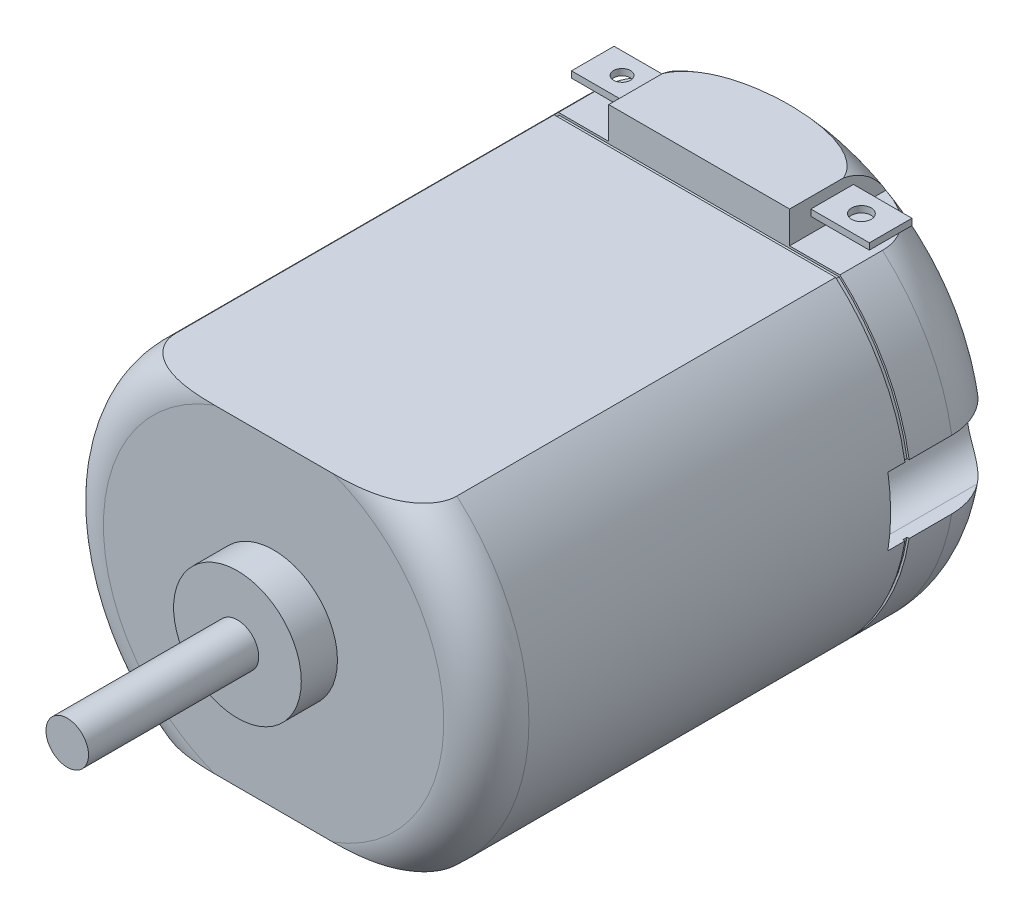
SolidWorks part; units mm, degrees
ref_plane "Спереди" through (0, 0, 0) normal (0, 0, 1) x (1, 0, 0)
ref_plane "Сверху" through (0, 0, 0) normal (0, 1, 0) x (1, 0, 0)
ref_plane "Справа" through (0, 0, 0) normal (1, 0, 0) x (0, 0, -1)
sketch "Эскиз1" plane through (0, 0, 0) normal (0, 0, 1) x (1, 0, 0)
  circle A0 centre (0, 0) radius 10
  dimension "D1" = 20
extrude "Бобышка-Вытянуть1" add sketch "Эскиз1" along normal blind 25
sketch "Эскиз2" plane through (0, 0, 0) normal (0, 0, 1) x (1, 0, 0)
  line L1 (12.9274, -7.5) -> (-12.9274, -7.5)
  line L2 (12.9274, -7.5) -> (12.9274, 7.5)
  line L3 (12.9274, 7.5) -> (-12.9274, 7.5)
  line L4 (-12.9274, -7.5) -> (-12.9274, 7.5)
  line L5 (12.9274, -7.5) -> (-12.9274, 7.5) construction
  line L6 (12.9274, 7.5) -> (-12.9274, -7.5) construction
  point P0 (0, 0)
  dimension "D1" = 15
extrude "Вырез-Вытянуть-Тонкостенный2" cut sketch "Эскиз2" along normal blind 25 from offset 5 thin thin type one direction wall 10
sketch "Эскиз3" plane through (0, 0, 25) normal (0, 0, 1) x (1, 0, 0)
  circle A0 centre (0, 0) radius 3
  dimension "D1" = 6
extrude "Бобышка-Вытянуть2" add sketch "Эскиз3" along normal blind 1.7
sketch "Эскиз4" plane through (0, 0, 26.7) normal (0, 0, 1) x (1, 0, 0)
  circle A0 centre (0, 0) radius 1
  dimension "D1" = 2
extrude "Бобышка-Вытянуть3" add sketch "Эскиз4" along normal blind 8
fillet "Скругление1" radius 2 2 edges at (10, 0, 25) (-10, 0, 25)
fillet "Скругление2" radius 3 1 edges at (10, 0, 0)
sketch "Эскиз5" plane through (0, 0, 0) normal (0, 0, -1) x (-1, 0, 0)
  line L0 (-3.5707, -3.5) -> (3.5707, -3.5)
  line L2 (-2.5, 3) -> (2.5, 3)
  line L3 (-2.5, 3) -> (-2.5, 2.2)
  line L4 (-2.5, 2.2) -> (2.5, 2.2)
  line L5 (2.5, 3) -> (2.5, 2.2)
  line L6 (-2.5, 3) -> (2.5, 2.2) construction
  line L7 (-2.5, 2.2) -> (2.5, 3) construction
  arc A0 (3.5707, -3.5) -> (-3.5707, -3.5) centre (0, 0) ccw
  point P5 (0, 2.6)
  dimension "D1" = 10
  dimension "D2" = 3.5
  dimension "D3" = 0.8
  dimension "D4" = 5
  dimension "D5" = 3
extrude "Бобышка-Вытянуть4" add sketch "Эскиз5" along normal blind 2
sketch "Эскиз6" plane through (0, 0, -2) normal (0, 0, -1) x (-1, 0, 0)
  circle A0 centre (0, 0) radius 1
  dimension "D1" = 2
extrude "Бобышка-Вытянуть5" add sketch "Эскиз6" along normal blind 1
sketch "Эскиз7" plane through (0, 0, 0) normal (0, 0, 1) x (1, 0, 0)
  line L0 (9.25, 0) -> (12.5108, 0) construction
  line L1 (9.25, 1.6) -> (12.5108, 1.6)
  line L2 (9.25, -1.6) -> (12.5108, -1.6)
  line L3 (-9.25, 0) -> (-13.1714, 0) construction
  line L4 (-9.25, -1.6) -> (-13.1714, -1.6)
  line L5 (-9.25, 1.6) -> (-13.1714, 1.6)
  circle A0 centre (0, 0) radius 9.25 construction
  arc A3 (9.25, 1.6) -> (9.25, -1.6) centre (9.25, 0) ccw
  arc A4 (12.5108, -1.6) -> (12.5108, 1.6) centre (12.5108, 0) ccw
  arc A5 (-9.25, -1.6) -> (-9.25, 1.6) centre (-9.25, 0) ccw
  arc A6 (-13.1714, 1.6) -> (-13.1714, -1.6) centre (-13.1714, 0) ccw
  point P5 (10.8804, 0)
  point P10 (-11.2107, 0)
  dimension "D1" = 18.5
  dimension "D2" = 1.6
extrude "Вырез-Вытянуть1" cut sketch "Эскиз7" along normal blind 6
sketch "Эскиз8" plane through (0, 0, 0) normal (0, 0, 1) x (1, 0, 0)
  line L0 (-6.6144, 7.5) -> (6.6144, 7.5)
  line L1 (6.6144, -7.5) -> (-6.6144, -7.5)
  arc A0 (-6.6144, 7.5) -> (-6.6144, -7.5) centre (0, 0) ccw construction
  arc A1 (-6.6144, 7.5) -> (-6.6144, -7.5) centre (0, 0) ccw
  arc A2 (6.6144, -7.5) -> (6.6144, 7.5) centre (0, 0) ccw construction
  arc A3 (6.6144, -7.5) -> (6.6144, 7.5) centre (0, 0) ccw
extrude "Вырез-Вытянуть-Тонкостенный3" cut sketch "Эскиз8" along normal blind 0.2 from offset 5 thin thin type mid plane wall 0.2
sketch "Эскиз9" plane through (0, 0, 0) normal (0, 0, 1) x (1, 0, 0)
  line L0 (-10.7949, -7.5) -> (11.3947, -7.5)
  line L1 (4.25, 9) -> (-4.25, 9)
  line L2 (4.25, 9) -> (4.25, 7.5)
  line L4 (-4.25, 9) -> (-4.25, 7.5)
  line L5 (-4.25, 7.5) -> (-7.5018, 7.5)
  line L6 (-7.5018, 7.5) -> (-7.5018, 11.8578)
  line L7 (6.6144, 7.5) -> (2.7839, 7.5) construction
  line L8 (-7.5018, 11.8578) -> (7.7203, 11.8578)
  line L9 (7.7203, 11.8578) -> (7.7203, 7.5)
  line L10 (7.7203, 7.5) -> (4.25, 7.5)
  line L11 (11.3947, -7.5) -> (11.3947, -11.8326)
  line L12 (11.3947, -11.8326) -> (-10.7949, -11.8326)
  line L13 (-10.7949, -11.8326) -> (-10.7949, -7.5)
  point P0 (0, 9)
  dimension "D1" = 8.5
  dimension "D2" = 1.5
extrude "Вырез-Вытянуть2" cut sketch "Эскиз9" along normal blind 5
sketch "Эскиз11" plane through (0, 0, 0) normal (1, 0, 0) x (0, 0, -1)
  line L1 (-4, 8.5) -> (-2, 8.5)
  line L2 (-4, 8.5) -> (-4, 8.2)
  line L3 (-4, 8.2) -> (-2, 8.2)
  line L4 (-2, 8.5) -> (-2, 8.2)
  dimension "D1" = 2
  dimension "D2" = 0.3
  dimension "D3" = 1
  dimension "D4" = 0.5
extrude "Бобышка-Вытянуть7" add sketch "Эскиз11" along normal blind 7 and the other way blind 7
sketch "Эскиз12" plane through (0, 8.5, 0) normal (0, 1, 0) x (1, 0, 0)
  line L0 (7, -2) -> (7, -4) construction
  line L1 (-7, -2) -> (-4.25, -2) construction
  line L2 (4.25, -2) -> (7, -2) construction
  circle A0 centre (5.625, -3) radius 0.4625
  circle A1 centre (-5.625, -3) radius 0.397
  point P7 (7, -3)
  point P11 (-5.625, -2)
  point P14 (5.625, -2)
extrude "Вырез-Вытянуть3" cut sketch "Эскиз12" against normal up to next
